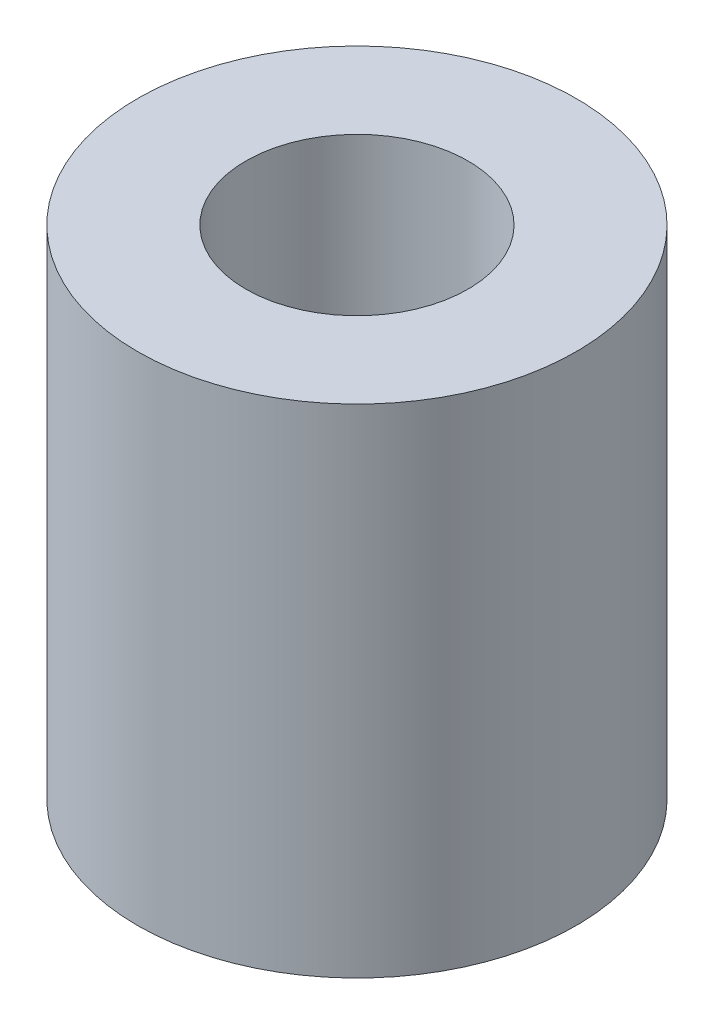
SolidWorks part; units mm, degrees
material "Nylon 101"
ref_plane "Front Plane" through (0, 0, 0) normal (0, 0, 1) x (1, 0, 0)
ref_plane "Top Plane" through (0, 0, 0) normal (0, 1, 0) x (1, 0, 0)
ref_plane "Right Plane" through (0, 0, 0) normal (1, 0, 0) x (0, 0, -1)
sketch "Sketch1" plane through (0, 0, 0) normal (0, 1, 0) x (1, 0, 0)
  circle A0 centre (0, 0) radius 9.525
  circle A1 centre (0, 0) radius 4.826
  dimension "D1" = 9.652
  dimension "D2" = 19.05
extrude "Boss-Extrude1" add sketch "Sketch1" along normal blind 21.59
